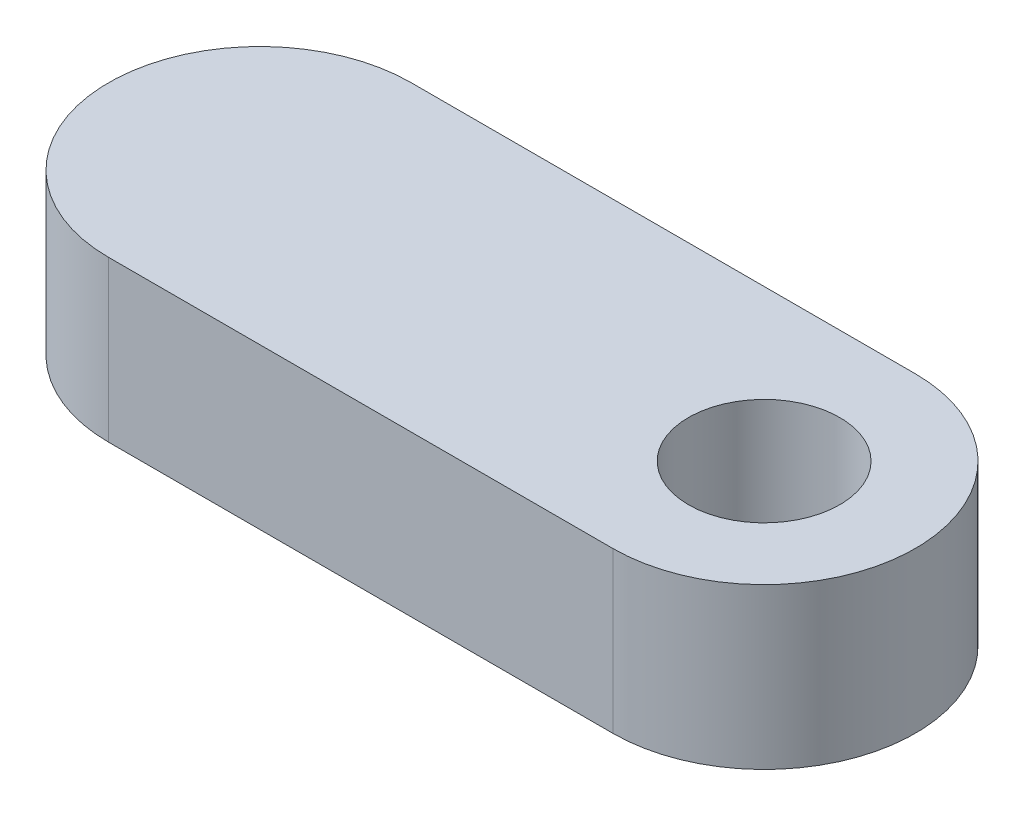
SolidWorks part; units mm, degrees
ref_plane "Front Plane" through (0, 0, 0) normal (0, 0, 1) x (1, 0, 0)
ref_plane "Top Plane" through (0, 0, 0) normal (0, 1, 0) x (1, 0, 0)
ref_plane "Right Plane" through (0, 0, 0) normal (1, 0, 0) x (0, 0, -1)
sketch "Sketch1" plane through (0, 0, 0) normal (0, 1, 0) x (1, 0, 0)
  line L0 (-5, 3) -> (5, 3)
  line L2 (5, -3) -> (-5, -3)
  line L3 (-8.8, 0) -> (8.8, 0) construction
  line L4 (0, -3.3) -> (0, 3.3) construction
  arc A0 (-5, 3) -> (-5, -3) centre (-5, 0) ccw
  arc A1 (5, 3) -> (5, -3) centre (5, 0) cw
  circle A2 centre (5, 0) radius 1.5
  dimension "D4" = 3
  dimension "D1" = 6
  dimension "D2" = 10
  dimension "D3" = 5
extrude "Boss-Extrude1" add sketch "Sketch1" along normal blind 3.175
equation "\"D3@Sketch1\"=\"D2@Sketch1\"/2"
